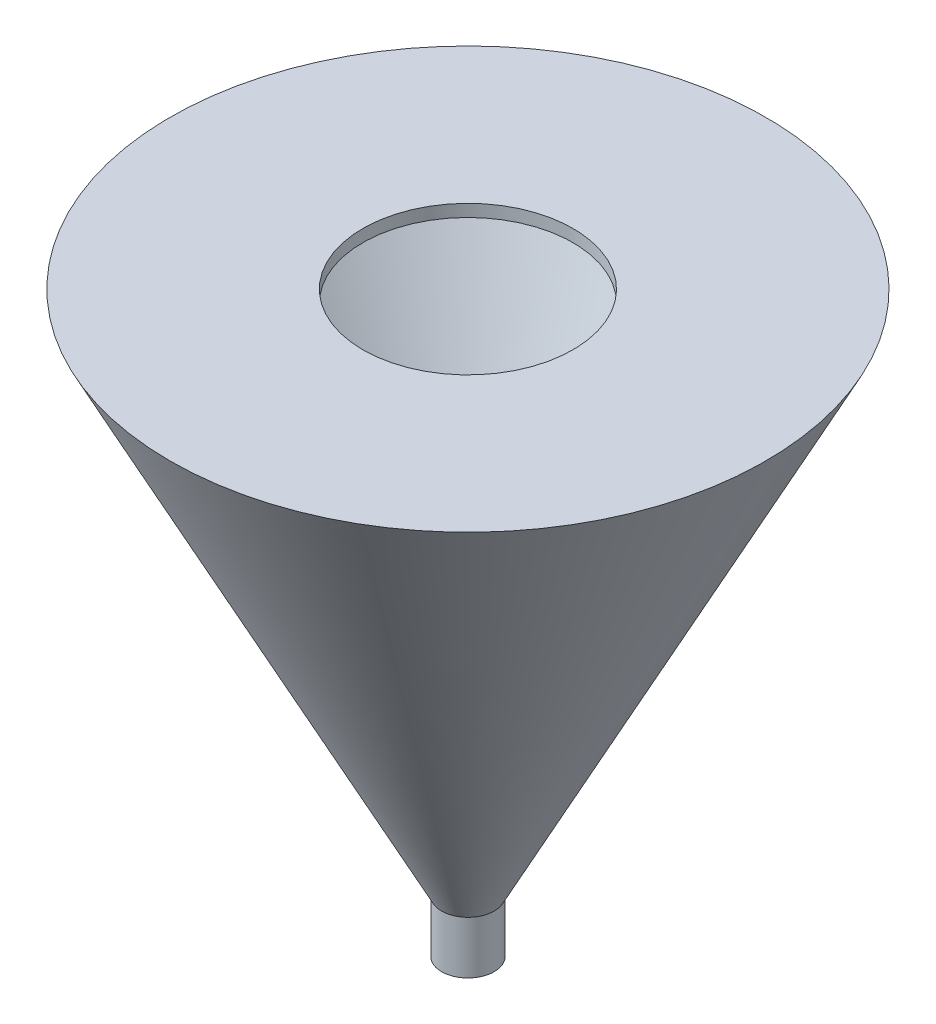
SolidWorks part; units mm, degrees
ref_plane "Alzado" through (0, 0, 0) normal (0, 0, 1) x (1, 0, 0)
ref_plane "Planta" through (0, 0, 0) normal (0, 1, 0) x (1, 0, 0)
ref_plane "Vista lateral" through (0, 0, 0) normal (1, 0, 0) x (0, 0, -1)
sketch "Croquis1" plane through (0, 0, 0) normal (0, 0, 1) x (1, 0, 0)
  line L1 (-7.5, 0) -> (-4.5, 0)
  line L2 (-7.5, 0) -> (-7.5, 15)
  line L3 (-7.5, 15) -> (-85, 165)
  line L4 (-85, 165) -> (-30, 165)
  line L5 (-30, 165) -> (-30, 161.5)
  line L6 (-30, 161.5) -> (-79.2521, 161.5)
  line L7 (-79.2521, 161.5) -> (-4.5, 16.8185)
  line L9 (-4.5, 16.8185) -> (-4.5, 0)
  line L10 (28.8092, 0) -> (-30.7641, 0) construction
  line L11 (0, 51.2913) -> (0, -41.7869) construction
  point P2 (-57.5, 165)
  dimension "D1" = 3.5
  dimension "D2" = 7.5
  dimension "D3" = 3
  dimension "D4" = 3.5
  dimension "D5" = 150
  dimension "D6" = 55
  dimension "D7" = 85
  dimension "D8" = 15
revolve "Revolución1" add sketch "Croquis1" angle 360 about L11
